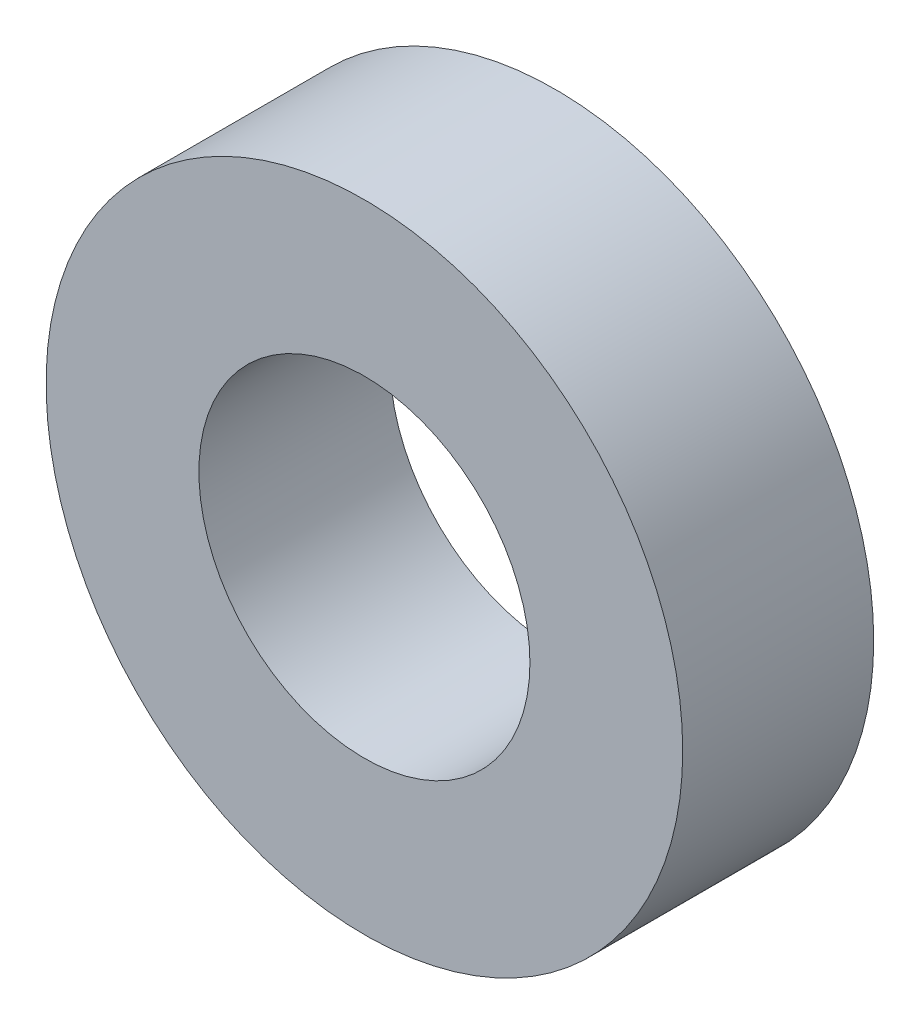
SolidWorks part; units mm, degrees
ref_plane "前视基准面" through (0, 0, 0) normal (0, 0, 1) x (1, 0, 0)
ref_plane "上视基准面" through (0, 0, 0) normal (0, 1, 0) x (1, 0, 0)
ref_plane "右视基准面" through (0, 0, 0) normal (1, 0, 0) x (0, 0, -1)
sketch "草图1" plane through (0, 0, 0) normal (0, 0, 1) x (1, 0, 0)
  circle A0 centre (0, 0) radius 2.6
  circle A1 centre (0, 0) radius 5
  dimension "D1" = 5.2
  dimension "D2" = 10
extrude "凸台-拉伸1" add sketch "草图1" along normal blind 3
